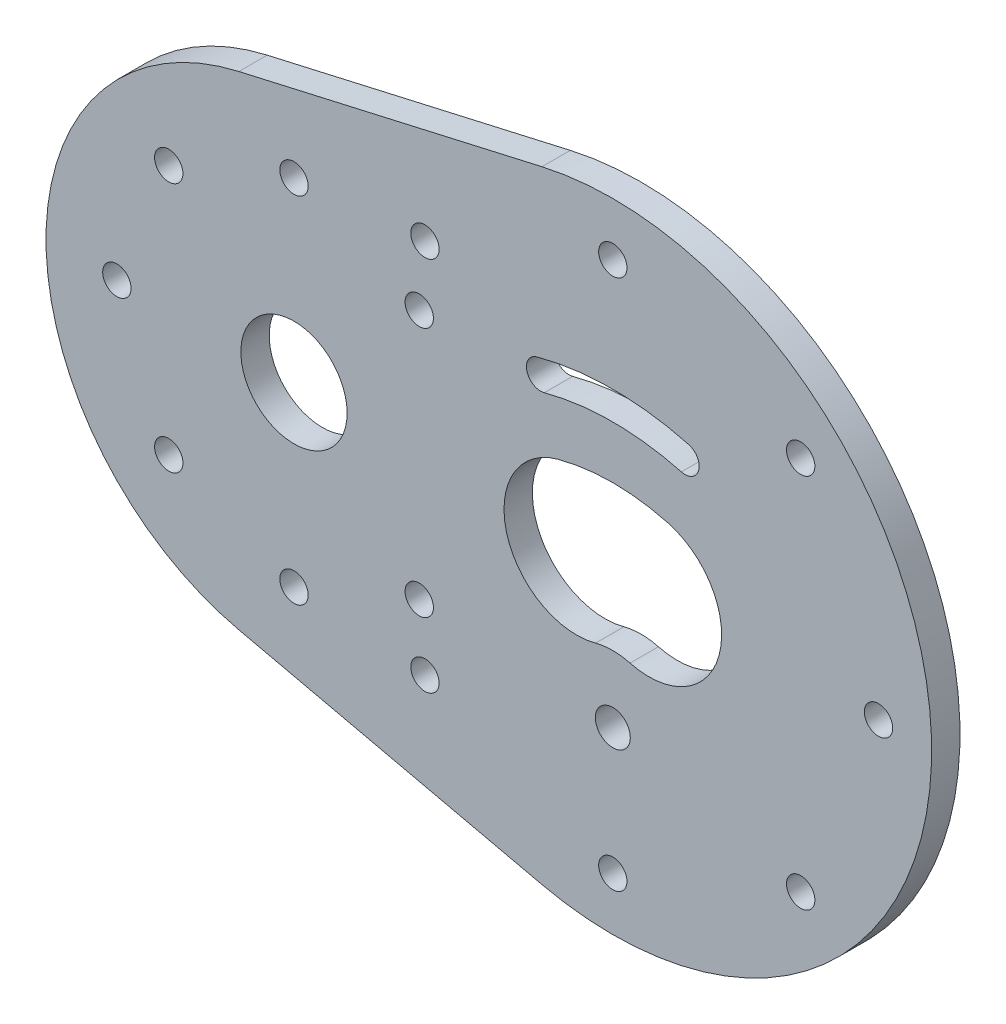
SolidWorks part; units mm, degrees
ref_plane "Front Plane" through (0, 0, 0) normal (0, 0, 1) x (1, 0, 0)
ref_plane "Top Plane" through (0, 0, 0) normal (0, 1, 0) x (1, 0, 0)
ref_plane "Right Plane" through (0, 0, 0) normal (1, 0, 0) x (0, 0, -1)
sketch "Sketch1" plane through (0, 0, 0) normal (0, 0, 1) x (1, 0, 0)
  line L0 (0, 0) -> (0, 36.4546) construction
  line L1 (0, 0) -> (-10.2847, 38.3829) construction
  line L2 (-28.575, 12.5) -> (0, 12.5) construction
  line L4 (-91.5313, 56.95) -> (35.4687, 56.95)
  line L5 (-91.5313, 56.95) -> (-91.5313, -31.95)
  line L6 (-91.5313, -31.95) -> (35.4687, -31.95)
  line L7 (35.4687, 56.95) -> (35.4687, -31.95)
  line L8 (-91.5313, 56.95) -> (35.4687, -31.95) construction
  line L9 (-91.5313, -31.95) -> (35.4687, 56.95) construction
  arc A0 (4.9215, 18.3672) -> (1.549, 5.781) centre (3.2352, 12.0741) cw
  arc A1 (4.9215, 18.3672) -> (-4.9215, 18.3672) centre (0, 0) ccw
  circle A2 centre (0, 12.5) radius 12.5 construction
  circle A3 centre (0, 0) radius 1.5649
  arc A4 (10.8253, 6.25) -> (-10.8253, 6.25) centre (0, 0) ccw construction
  arc A5 (1.549, 5.781) -> (-1.549, 5.781) centre (0, 0) ccw
  arc A6 (-4.9215, 18.3672) -> (-1.549, 5.781) centre (-3.2352, 12.0741) ccw
  circle A7 centre (0, 25) radius 1.27 construction
  arc A8 (6.7992, 25.3749) -> (-6.7992, 25.3749) centre (0, 0) ccw
  arc A9 (6.1418, 22.9214) -> (-6.1418, 22.9214) centre (0, 0) ccw
  circle A10 centre (0, 0) radius 25 construction
  arc A11 (-6.7992, 25.3749) -> (-6.1418, 22.9214) centre (-6.4705, 24.1481) ccw
  arc A12 (6.7992, 25.3749) -> (6.1418, 22.9214) centre (6.4705, 24.1481) cw
  circle A13 centre (-28.575, 12.5) radius 4.7625
  circle A14 centre (-28.575, 12.5) radius 25.4 construction
  point P0 (0, 0)
  point P18 (-28.0313, 12.5)
  dimension "D4" = 25
  dimension "D6" = 50.8
  dimension "D2" = 2.54
  dimension "D3" = 9.525
  dimension "D1" = 15
  dimension "D5" = 28.575
  dimension "D7" = 88.9
  dimension "D8" = 127
extrude "Boss-Extrude1" add sketch "Sketch1" along normal blind 2.54
sketch "Sketch2" plane through (0, 0, 2.54) normal (0, 0, 1) x (1, 0, 0)
  line L0 (-28.575, 12.5) -> (43.934, 12.5) construction
  line L1 (0, 0) -> (0, 70.9306) construction
  line L2 (-33.5139, 34.1693) -> (-6.35, 40.3605)
  line L3 (-33.5139, -9.1693) -> (-6.35, -15.3605)
  line L5 (-107.0175, 80.3674) -> (70.5021, 80.3674)
  line L6 (-107.0175, 80.3674) -> (-107.0175, -46.3508)
  line L7 (-107.0175, -46.3508) -> (70.5021, -46.3508)
  line L8 (70.5021, 80.3674) -> (70.5021, -46.3508)
  arc A0 (-6.35, -15.3605) -> (-6.35, 40.3605) centre (0, 12.5) ccw
  arc A1 (-33.5139, 34.1693) -> (-33.5139, -9.1693) centre (-28.575, 12.5) ccw
  dimension "D1" = 57.15
  dimension "D2" = 44.45
extrude "Cut-Extrude1" cut sketch "Sketch2" against normal through all
sketch "Sketch4" plane through (0, 0, 2.54) normal (0, 0, 1) x (1, 0, 0)
  line L0 (-28.575, 12.5) -> (35.849, 12.5) construction
  line L1 (0, 0) -> (0, 48.1146) construction
  circle A0 centre (-28.575, 12.5) radius 15.875 construction
  circle A1 centre (0, 12.5) radius 23.8125 construction
  circle A2 centre (-28.575, 28.375) radius 1.27
  circle A3 centre (0, 36.3125) radius 1.27
  circle A4 centre (-17.3497, 23.7253) radius 1.27
  circle A5 centre (-12.7, 12.5) radius 1.27 [skipped]
  circle A6 centre (-17.3497, 1.2747) radius 1.27
  circle A7 centre (-28.575, -3.375) radius 1.27
  circle A8 centre (-39.8003, 1.2747) radius 1.27
  circle A9 centre (-44.45, 12.5) radius 1.27
  circle A10 centre (-39.8003, 23.7253) radius 1.27
  circle A11 centre (16.838, 29.338) radius 1.27
  circle A12 centre (23.8125, 12.5) radius 1.27
  circle A13 centre (16.838, -4.338) radius 1.27
  circle A14 centre (0, -11.3125) radius 1.27
  circle A15 centre (-16.838, -4.338) radius 1.27
  circle A16 centre (-23.8125, 12.5) radius 1.27 [skipped]
  circle A17 centre (-16.838, 29.338) radius 1.27
  dimension "D1" = 47.625
  dimension "D2" = 31.75
  dimension "D3" = 2.54
  dimension "D4" = 2.54
  dimension "D5" = 8
  dimension "D6" = 8
extrude "Cut-Extrude2" cut sketch "Sketch4" against normal through all
